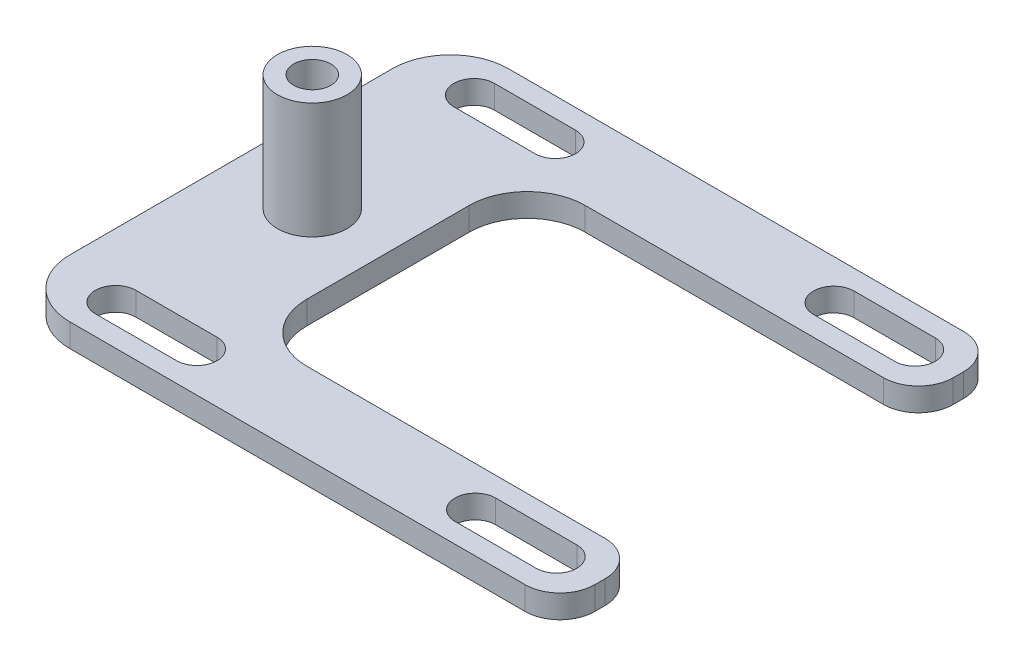
SolidWorks part; units mm, degrees
ref_plane "Front Plane" through (0, 0, 0) normal (0, 0, 1) x (1, 0, 0)
ref_plane "Top Plane" through (0, 0, 0) normal (0, 1, 0) x (1, 0, 0)
ref_plane "Right Plane" through (0, 0, 0) normal (1, 0, 0) x (0, 0, -1)
sketch "Sketch1" plane through (0, 0, 0) normal (0, 1, 0) x (1, 0, 0)
  line L0 (47.2433, 30.9) -> (47.2433, 37.8)
  line L1 (47.2433, 6.9) -> (13.5188, 6.9)
  line L3 (47.2433, 30.9) -> (13.5188, 30.9)
  line L4 (13.5188, 6.9) -> (13.5188, 30.9)
  line L5 (5.4933, 34.35) -> (12.4933, 34.35) construction
  line L6 (5.4933, 36.1) -> (12.4933, 36.1)
  line L7 (47.2433, 0) -> (0, 0)
  line L9 (47.2433, 37.8) -> (0, 37.8)
  line L10 (0, 0) -> (0, 37.8)
  line L11 (5.4933, 32.6) -> (12.4933, 32.6)
  line L12 (36.4933, 34.35) -> (43.4933, 34.35) construction
  line L13 (47.2433, 6.9) -> (47.2433, 0)
  line L14 (36.4933, 36.1) -> (43.4933, 36.1)
  line L15 (36.4933, 32.6) -> (43.4933, 32.6)
  line L16 (5.4933, 3.45) -> (12.4933, 3.45) construction
  line L17 (5.4933, 5.2) -> (12.4933, 5.2)
  line L18 (5.4933, 1.7) -> (12.4933, 1.7)
  line L19 (36.4933, 3.45) -> (43.4933, 3.45) construction
  line L20 (36.4933, 5.2) -> (43.4933, 5.2)
  line L21 (36.4933, 1.7) -> (43.4933, 1.7)
  line L22 (8.9933, 34.35) -> (39.9933, 3.45) construction
  line L23 (39.9933, 34.35) -> (8.9933, 3.45) construction
  arc A0 (5.4933, 36.1) -> (5.4933, 32.6) centre (5.4933, 34.35) ccw
  arc A1 (12.4933, 32.6) -> (12.4933, 36.1) centre (12.4933, 34.35) ccw
  arc A2 (36.4933, 36.1) -> (36.4933, 32.6) centre (36.4933, 34.35) ccw
  arc A3 (43.4933, 32.6) -> (43.4933, 36.1) centre (43.4933, 34.35) ccw
  arc A4 (5.4933, 5.2) -> (5.4933, 1.7) centre (5.4933, 3.45) ccw
  arc A5 (12.4933, 1.7) -> (12.4933, 5.2) centre (12.4933, 3.45) ccw
  arc A6 (36.4933, 5.2) -> (36.4933, 1.7) centre (36.4933, 3.45) ccw
  arc A7 (43.4933, 1.7) -> (43.4933, 5.2) centre (43.4933, 3.45) ccw
  point P0 (0, 0)
  point P6 (0, 0)
  point P8 (8.9933, 34.35)
  point P18 (39.9933, 34.35)
  point P25 (8.9933, 3.45)
  point P32 (39.9933, 3.45)
  point P39 (47.2433, 34.35)
  point P40 (47.2433, 3.45)
  point P43 (45.2433, 34.35)
  dimension "D3" = 1.75
  dimension "D1" = 6.9
  dimension "D2" = 7
  dimension "D4" = 38
  dimension "D5" = 2
  dimension "D6" = 30.9
extrude "Boss-Extrude1" add sketch "Sketch1" along normal blind 2
fillet "Fillet1" radius 5 4 edges at (0, 1, -37.8) (0, 1, 0) (13.5188, 1, -6.9) (13.5188, 1, -30.9)
fillet "Fillet2" radius 3 4 edges at (47.2433, 1, -6.9) (47.2433, 1, 0) (47.2433, 1, -30.9) (47.2433, 1, -37.8)
sketch "Sketch2" plane through (0, 2, 0) normal (0, 1, 0) x (1, 0, 0)
  line L0 (0, 32.8) -> (0, 5) construction
  line L2 (12.4933, 6.9) -> (36.4933, 6.9) construction
  line L3 (12.4933, 6.9) -> (12.4933, 30.9) construction
  line L4 (12.4933, 30.9) -> (36.4933, 30.9) construction
  line L5 (36.4933, 6.9) -> (36.4933, 30.9) construction
  line L6 (12.4933, 6.9) -> (36.4933, 30.9) construction
  line L7 (12.4933, 30.9) -> (36.4933, 6.9) construction
  circle A0 centre (6.9933, 18.9) radius 3
  circle A1 centre (6.9933, 18.9) radius 1.6
  point P3 (0, 0)
  point P6 (0, 18.9)
  point P7 (24.4933, 18.9)
  dimension "D1" = 3.2
  dimension "D2" = 6
  dimension "D3" = 24
  dimension "D4" = 24
  dimension "D5" = 17.5
extrude "Boss-Extrude2" add sketch "Sketch2" along normal blind 10
